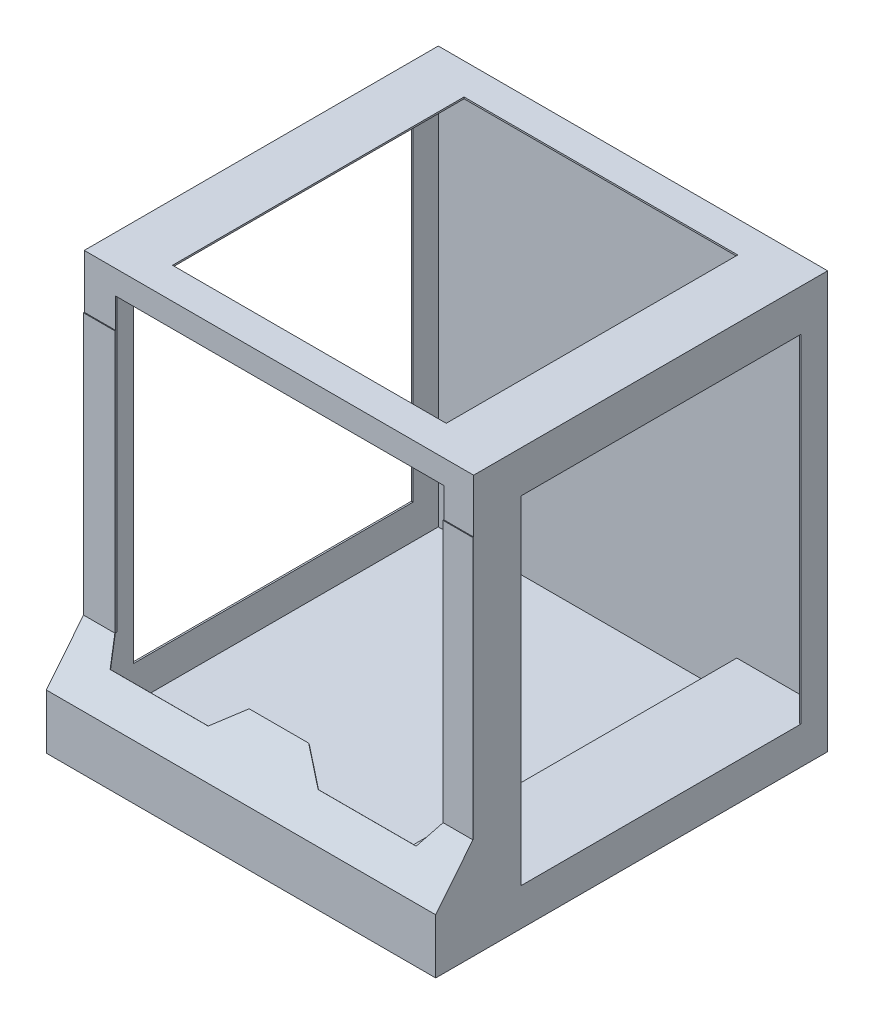
SolidWorks part; units mm, degrees
ref_plane "Front Plane" through (0, 0, 0) normal (0, 0, 1) x (1, 0, 0)
ref_plane "Top Plane" through (0, 0, 0) normal (0, 1, 0) x (1, 0, 0)
ref_plane "Right Plane" through (0, 0, 0) normal (1, 0, 0) x (0, 0, -1)
sketch "Sketch2" plane through (0, 0, 0) normal (1, 0, 0) x (0, 0, -1)
  line L0 (657.578, 700) -> (62.578, 700)
  line L1 (62.578, 700) -> (62.578, 170)
  line L2 (62.578, 170) -> (0, 92)
  line L3 (0, 92) -> (0, 0)
  line L4 (0, 0) -> (657.578, 0)
  line L5 (657.578, 0) -> (657.578, 700)
  dimension "D1" = 595
  dimension "D2" = 700
  dimension "D3" = 530
  dimension "D4" = 100
  dimension "D5" = 92
extrude "Boss-Extrude2" add sketch "Sketch2" along normal blind 2.7 contours L0 L1 L2 L3 L4 L5
ref_plane "Plane2" through (651.7, 0, 0) normal (1, 0, 0) x (0, 0, -1)
sketch "Sketch4" plane through (651.7, 0, 0) normal (1, 0, 0) x (0, 0, -1)
  line L0 (657.578, 700) -> (62.578, 700)
  line L1 (62.578, 700) -> (62.578, 170)
  line L2 (62.578, 170) -> (0, 92)
  line L3 (0, 92) -> (0, 0)
  line L4 (0, 0) -> (657.578, 0)
  line L5 (657.578, 0) -> (657.578, 700)
  dimension "D1" = 595
  dimension "D2" = 700
  dimension "D3" = 530
  dimension "D4" = 92
  dimension "D5" = 100
extrude "Boss-Extrude3" add sketch "Sketch4" along normal blind 2.7 separate body
sketch "Sketch5" plane through (0, 0, 0) normal (0, 1, 0) x (1, 0, 0)
  line L1 (0, 657.578) -> (654.4, 657.578)
  line L2 (0, 657.578) -> (0, 0)
  line L3 (0, 0) -> (654.4, 0)
  line L4 (654.4, 657.578) -> (654.4, 0)
  line L5 (0, 657.578) -> (654.4, 0) construction
  line L6 (0, 0) -> (654.4, 657.578) construction
  point P4 (327.2, 328.789)
extrude "Boss-Extrude4" add sketch "Sketch5" along normal blind 2.7
ref_plane "Plane3" through (0, 700, 0) normal (0, -1, 0) x (-1, 0, 0)
sketch "Sketch6" plane through (0, 700, 0) normal (0, -1, 0) x (-1, 0, 0)
  line L1 (-654.4, 657.578) -> (0, 657.578)
  line L2 (-654.4, 657.578) -> (-654.4, 62.578)
  line L3 (-654.4, 62.578) -> (0, 62.578)
  line L4 (0, 657.578) -> (0, 62.578)
  line L5 (-654.4, 657.578) -> (0, 62.578) construction
  line L6 (-654.4, 62.578) -> (0, 657.578) construction
  point P4 (-327.2, 360.078)
extrude "Boss-Extrude5" add sketch "Sketch6" along normal blind 2.7
ref_plane "Plane4" through (0, 0, -657.6) normal (0, 0, 1) x (1, 0, 0)
ref_plane "Plane5" through (2.7, 2.7, -657.578) normal (-1, 0, 0) x (0, 0, 1)
sketch "Sketch10" plane through (0, 0, -657.6) normal (0, 0, 1) x (1, 0, 0)
  line L0 (-359.92, 700) -> (359.92, 700) construction
  line L1 (2.7, 700) -> (651.7, 700)
  line L2 (2.7, 700) -> (2.7, 0)
  line L3 (2.7, 0) -> (651.7, 0)
  line L4 (651.7, 700) -> (651.7, 0)
  line L5 (2.7, 700) -> (651.7, 0) construction
  line L6 (2.7, 0) -> (651.7, 700) construction
  line L7 (651.7, -361.6679) -> (651.7, 361.6679) construction
  point P4 (327.2, 350)
  dimension "D1" = 649
  dimension "D2" = 700
extrude "Boss-Extrude6" add sketch "Sketch10" along normal blind 2.7
sketch "Sketch11" plane through (0, 0, 0) normal (-1, 0, 0) x (0, 0, 1)
  line L1 (-612.578, 60) -> (-142.578, 60)
  line L2 (-612.578, 60) -> (-612.578, 630)
  line L3 (-612.578, 630) -> (-142.578, 630)
  line L4 (-142.578, 60) -> (-142.578, 630)
  line L5 (-612.578, 60) -> (-142.578, 630) construction
  line L6 (0, 92) -> (-62.578, 170)
  line L7 (-62.578, 170) -> (-62.578, 700)
  line L8 (-62.578, 700) -> (-657.578, 700)
  line L9 (-657.578, 700) -> (-657.578, 0)
  line L10 (-657.578, 0) -> (0, 0)
  line L11 (0, 0) -> (0, 92)
  line L12 (0, 92) -> (-62.578, 170)
  line L13 (-62.578, 170) -> (-62.578, 700)
  line L14 (-62.578, 700) -> (-657.578, 700)
  line L15 (-657.578, 700) -> (-657.578, 0)
  line L16 (-657.578, 0) -> (0, 0)
  line L17 (0, 0) -> (0, 92)
  line L18 (-612.578, 630) -> (-142.578, 60) construction
  point P2 (-612.578, 60)
  point P11 (-377.578, 345)
  dimension "D2" = 60
  dimension "D3" = 45
  dimension "D4" = 570
  dimension "D5" = 470
  dimension "D1" = 0
extrude "Cut-Extrude2" cut sketch "Sketch11" against normal through all contours L2 L1 L4 L3
sketch "Sketch12" plane through (0, 700, 0) normal (0, 1, 0) x (1, 0, 0)
  line L3 (95.85, 115.078) -> (555.85, 115.078)
  line L4 (95.85, 115.078) -> (95.85, 605.078)
  line L5 (95.85, 605.078) -> (555.85, 605.078)
  line L6 (555.85, 115.078) -> (555.85, 605.078)
  line L7 (95.85, 115.078) -> (555.85, 605.078) construction
  line L8 (95.85, 605.078) -> (555.85, 115.078) construction
  line L12 (654.4, 62.578) -> (0, 62.578) construction
  line L14 (0, 657.578) -> (0, 62.578) construction
  point P9 (325.85, 360.078)
  dimension "D1" = 52.5
  dimension "D2" = 95.85
  dimension "D3" = 490
  dimension "D4" = 460
extrude "Cut-Extrude3" cut sketch "Sketch12" against normal up to next
sketch "Sketch13" plane through (0, 0, -62.578) normal (0, 0, 1) x (1, 0, 0)
  line L0 (2.7, 700) -> (2.7, 170)
  line L2 (2.7, 170) -> (52.7, 170)
  line L3 (52.7, 170) -> (52.7, 660)
  line L4 (52.7, 660) -> (604.4, 660)
  line L5 (604.4, 660) -> (604.4, 170)
  line L6 (604.4, 170) -> (654.4, 170)
  line L7 (654.4, 170) -> (654.4, 700)
  line L8 (654.4, 700) -> (2.7, 700)
  dimension "D1" = 40
  dimension "D2" = 50
  dimension "D3" = 50
extrude "Boss-Extrude8" add sketch "Sketch13" against normal blind 2.7
sketch "Sketch14" plane through (0, 0, 0) normal (-1, 0, 0) x (0, 0, 1)
  line L0 (-62.578, 170) -> (-62.578, 171.4)
  line L1 (-62.578, 700) -> (-62.578, 170) construction
  line L2 (-62.578, 171.4) -> (1.1232, 92)
  line L3 (1.1232, 92) -> (1.1232, 0)
  line L4 (-62.578, 170) -> (0, 92) construction
  line L5 (0, 92) -> (0, 0) construction
  line L6 (1.1232, 0) -> (0, 0)
  line L7 (0, 0) -> (0, 92)
  line L8 (0, 92) -> (-62.578, 170)
  dimension "D1" = 1.4
extrude "Boss-Extrude10" add sketch "Sketch14" against normal up to surface (654.4 mm away) separate body up to face at (654.4, 277, -240.052)
sketch "Sketch15" plane through (0, 0, 0) normal (-1, 0, 0) x (0, 0, 1)
  line L0 (-62.578, 170) -> (-62.578, 610)
  line L1 (-62.578, 700) -> (-62.578, 170) construction
  line L2 (-62.578, 610) -> (-61.178, 610)
  line L3 (-61.178, 610) -> (-61.178, 170)
  line L4 (-61.178, 170) -> (-62.578, 170)
  line L6 (-62.578, 700) -> (-62.578, 610) construction
  dimension "D1" = 1.4
  dimension "D2" = 1.4
  dimension "D3" = 90
extrude "Boss-Extrude12" add sketch "Sketch15" against normal up to vertex (52.7 mm away) separate body
ref_plane "Plane6" through (327.2, 0, 0) normal (-1, 0, 0) x (0, 0, 1)
pattern_linear "LPattern1" count 2 spacing 604.4 along (1, 0, 0) of "Boss-Extrude12"
sketch "Sketch16" plane through (654.4, 0, 0) normal (1, 0, 0) x (0, 0, -1)
  line L1 (-59.9329, 727.4468) -> (294.4268, 727.4468)
  line L2 (-59.9329, 727.4468) -> (-59.9329, -44.6279)
  line L3 (-59.9329, -44.6279) -> (294.4268, -44.6279)
  line L4 (294.4268, 727.4468) -> (294.4268, -44.6279)
  line L5 (-59.9329, 727.4468) -> (294.4268, -44.6279) construction
  line L6 (-59.9329, -44.6279) -> (294.4268, 727.4468) construction
  point P4 (117.247, 341.4095)
extrude "Cut-Extrude5" cut sketch "Sketch16" along normal blind 55
sketch "Sketch17" plane through (0, 36.5754, 45.5893) normal (0, 0.6258, 0.78) x (1, 0, 0)
  line L0 (52.7, 170.8839) -> (70, 130.4256)
  line L1 (70, 130.4256) -> (234.7736, 130.4256)
  line L2 (234.7736, 130.4256) -> (277.2, 172.852)
  line L3 (654.4, 172.852) -> (0, 172.852) construction
  line L4 (277.2, 172.852) -> (377.2, 172.852)
  line L5 (377.2, 172.852) -> (419.6264, 130.4256)
  line L6 (419.6264, 130.4256) -> (584.4, 130.4256)
  line L7 (584.4, 130.4256) -> (604.4, 170.8839)
  line L8 (604.4, 170.8839) -> (604.4, 298.9302)
  line L9 (604.4, 170.8839) -> (604.4, 514.0839) construction
  line L10 (604.4, 298.9302) -> (52.7, 298.9302)
  line L11 (52.7, 170.8839) -> (52.7, 514.0839) construction
  line L12 (52.7, 298.9302) -> (52.7, 170.8839)
  line L18 (327.2, 361.6679) -> (327.2, -361.6679) construction
  line L19 (0, 71.0571) -> (0, 172.852) construction
  line L20 (654.4, 172.852) -> (654.4, 71.0571) construction
  dimension "D1" = 100
  dimension "D2" = 60
  dimension "D3" = 60
  dimension "D4" = 50
  dimension "D5" = 70
  dimension "D6" = 70
extrude "Cut-Extrude6" cut sketch "Sketch17" against normal blind 25
sketch "Sketch19" plane through (0, 2.7, 0) normal (0, 1, 0) x (1, 0, 0)
  line L0 (654.4, 62.578) -> (654.4, -1.1232) construction
  line L1 (654.4, 657.6) -> (504.4, 657.6)
  line L2 (654.4, 657.6) -> (654.4, 2.6)
  line L3 (654.4, 2.6) -> (504.4, 2.6)
  line L4 (504.4, 657.6) -> (504.4, 2.6)
  line L5 (654.4, 657.6) -> (504.4, 2.6) construction
  line L6 (654.4, 2.6) -> (504.4, 657.6) construction
  line L7 (2.7, 657.6) -> (651.7, 657.6) construction
  point P4 (579.4, 330.1)
  dimension "D1" = 150
  dimension "D2" = 655
extrude "Boss-Extrude13" add sketch "Sketch19" along normal blind 60
ref_plane "Plane7" through (2.7, 2.7, 0) normal (0, 0, 1) x (1, 0, 0)
